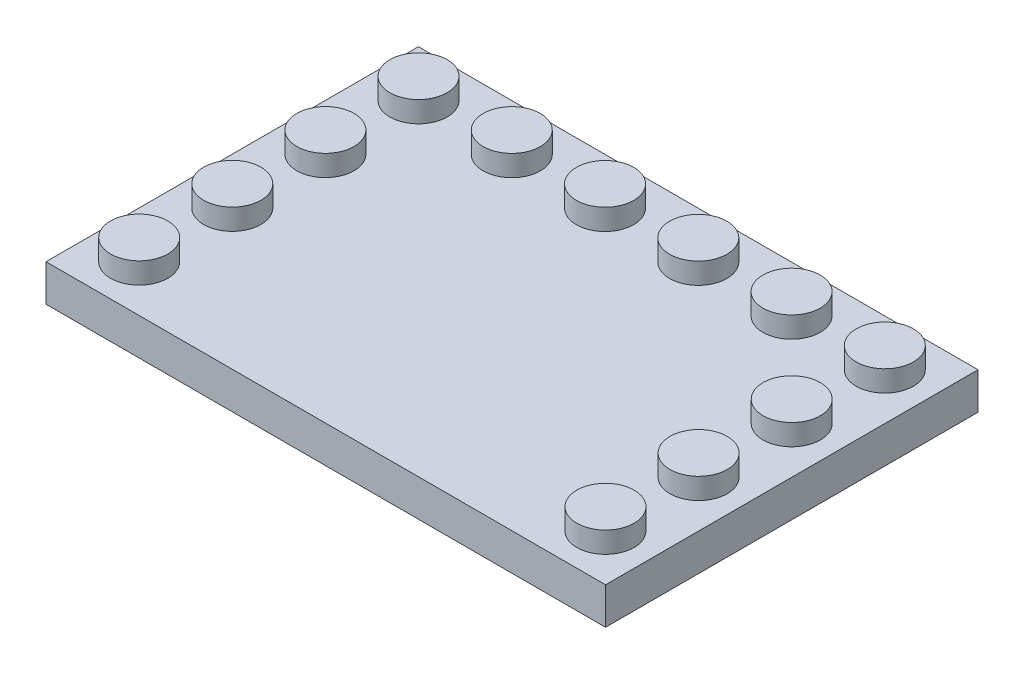
SolidWorks part; units mm, degrees
ref_plane "Front Plane" through (0, 0, 0) normal (0, 0, 1) x (1, 0, 0)
ref_plane "Top Plane" through (0, 0, 0) normal (0, 1, 0) x (1, 0, 0)
ref_plane "Right Plane" through (0, 0, 0) normal (1, 0, 0) x (0, 0, -1)
sketch "Sketch1" plane through (0, 0, 0) normal (0, 1, 0) x (1, 0, 0)
  line L1 (-23.925, 15.925) -> (23.925, 15.925)
  line L2 (-23.925, 15.925) -> (-23.925, -15.925)
  line L3 (-23.925, -15.925) -> (23.925, -15.925)
  line L4 (23.925, 15.925) -> (23.925, -15.925)
  line L5 (-23.925, 15.925) -> (23.925, -15.925) construction
  line L6 (-23.925, -15.925) -> (23.925, 15.925) construction
  point P0 (0, 0)
  dimension "D1" = 31.85
  dimension "D2" = 47.85
extrude "Boss-Extrude1" add sketch "Sketch1" against normal blind 3.15
sketch "Sketch2" plane through (0, 0, 0) normal (0, 1, 0) x (1, 0, 0)
  line L1 (-23.925, 15.925) -> (-23.925, -15.925) construction
  line L2 (-23.925, -15.925) -> (23.925, -15.925) construction
  circle A0 centre (-19.9375, -11.9438) radius 2.45
  circle A1 centre (-19.9375, -3.9813) radius 2.45
  circle A2 centre (-19.9375, 3.9812) radius 2.45
  circle A3 centre (-19.9375, 11.9437) radius 2.45
  circle A4 centre (-11.9625, 11.9437) radius 2.45
  circle A5 centre (-3.9875, 11.9437) radius 2.45
  circle A6 centre (3.9875, 11.9437) radius 2.45
  circle A7 centre (11.9625, 11.9437) radius 2.45
  circle A8 centre (19.9375, 11.9437) radius 2.45
  circle A9 centre (19.9375, 3.9812) radius 2.45
  circle A10 centre (19.9375, -3.9813) radius 2.45
  circle A11 centre (19.9375, -11.9438) radius 2.45
  dimension "D1" = 4.9
  dimension "D5" = 7.9625
  dimension "D7" = 7.975
  dimension "D9" = 7.9625
  dimension "D2" = 3.9875
  dimension "D3" = 3.9813
  dimension "D6" = 6
  dimension "D4" = 4
  dimension "D8" = 4
extrude "Boss-Extrude2" add sketch "Sketch2" along normal blind 1.8
shell "Shell1" thickness 1.5
sketch "Sketch3" plane through (0, -1.5, 0) normal (0, -1, 0) x (1, 0, 0)
  line L0 (-23.925, -15.925) -> (-23.925, 15.925) construction
  line L1 (23.925, -15.925) -> (-23.925, -15.925) construction
  line L5 (23.925, 15.925) -> (23.925, -15.925) construction
  circle A0 centre (-15.95, -7.9625) radius 3.25
  circle A1 centre (-15.95, -7.9625) radius 2.35
  circle A2 centre (-7.975, -7.9625) radius 2.35
  circle A3 centre (-7.975, -7.9625) radius 3.25
  circle A4 centre (0, -7.9625) radius 2.35
  circle A5 centre (0, -7.9625) radius 3.25
  circle A6 centre (7.975, -7.9625) radius 2.35
  circle A7 centre (7.975, -7.9625) radius 3.25
  circle A8 centre (15.95, -7.9625) radius 2.35
  circle A9 centre (15.95, -7.9625) radius 3.25
  circle A10 centre (-7.975, 0) radius 2.35
  circle A11 centre (-7.975, 0) radius 3.25
  circle A12 centre (0, 0) radius 2.35
  circle A13 centre (0, 0) radius 3.25
  circle A14 centre (7.975, 0) radius 2.35
  circle A15 centre (7.975, 0) radius 3.25
  circle A16 centre (15.95, 0) radius 2.35
  circle A17 centre (15.95, 0) radius 3.25
  circle A18 centre (-7.975, 7.9625) radius 2.35
  circle A19 centre (-7.975, 7.9625) radius 3.25
  circle A20 centre (0, 7.9625) radius 2.35
  circle A21 centre (0, 7.9625) radius 3.25
  circle A22 centre (7.975, 7.9625) radius 2.35
  circle A23 centre (7.975, 7.9625) radius 3.25
  circle A24 centre (15.95, 7.9625) radius 2.35
  circle A25 centre (15.95, 7.9625) radius 3.25
  circle A26 centre (-15.95, 0) radius 2.35
  circle A27 centre (-15.95, 0) radius 3.25
  circle A28 centre (-15.95, 7.9625) radius 2.35
  circle A29 centre (-15.95, 7.9625) radius 3.25
  dimension "D1" = 6.5
  dimension "D2" = 4.7
  dimension "D3" = 7.975
  dimension "D4" = 7.9625
  dimension "D7" = 7.975
  dimension "D8" = 7.9625
  dimension "D9" = 7.975
  dimension "D5" = 5
  dimension "D6" = 3
extrude "Boss-Extrude3" add sketch "Sketch3" along normal offset from surface (1.45 mm away) 0.2 up to face at (0, -3.15, 0)
